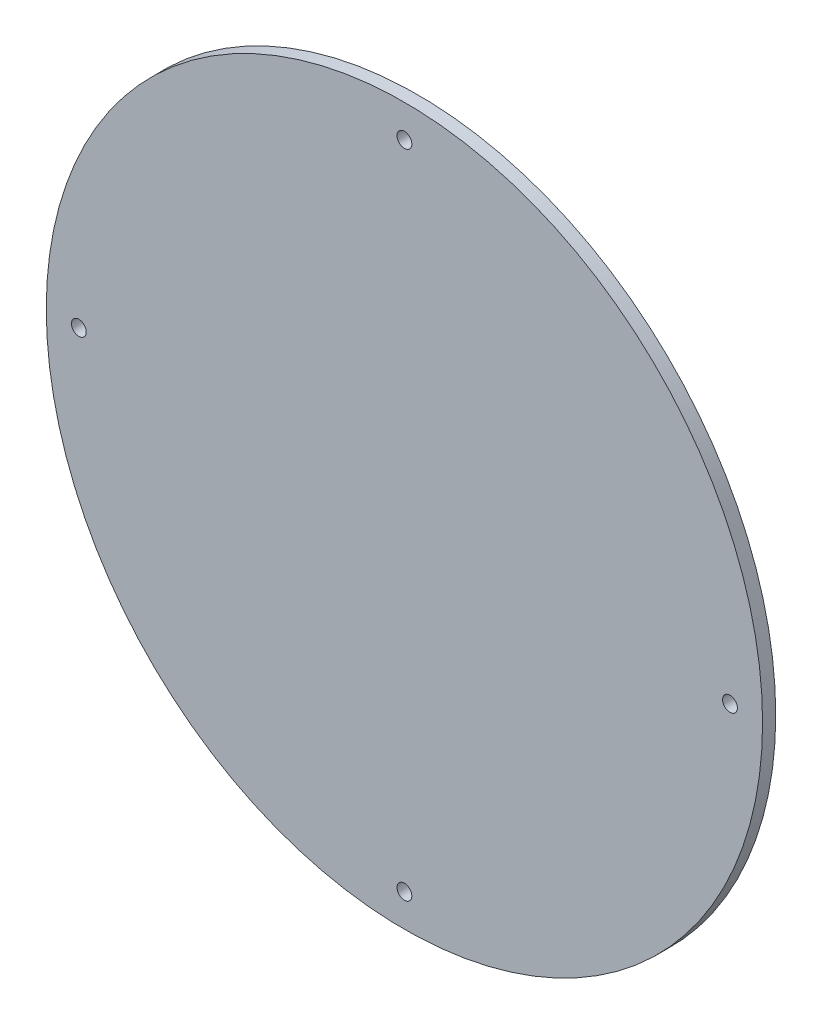
SolidWorks part; units mm, degrees
ref_plane "Front Plane" through (0, 0, 0) normal (0, 0, 1) x (1, 0, 0)
ref_plane "Top Plane" through (0, 0, 0) normal (0, 1, 0) x (1, 0, 0)
ref_plane "Right Plane" through (0, 0, 0) normal (1, 0, 0) x (0, 0, -1)
sketch "Sketch1" plane through (0, 0, 0) normal (0, 0, 1) x (1, 0, 0)
  line L0 (0, 78.5) -> (0, 0) construction
  line L1 (-78.5, 0) -> (-1.5065, 0) construction
  circle A0 centre (0, 0) radius 86.36
  circle A1 centre (0, 78.5) radius 1.7859
  circle A2 centre (78.5, 0) radius 1.7859
  circle A3 centre (0, -78.5) radius 1.7859
  circle A4 centre (-78.5, 0) radius 1.7859
  point P14 (0, 0)
  dimension "D1" = 172.72
  dimension "D2" = 3.5719
  dimension "D3" = 78.5
  dimension "D5" = 78.5
  dimension "D4" = 4
extrude "Boss-Extrude1" add sketch "Sketch1" along normal blind 3.175 contours A0 A4 A3 A2 A1
